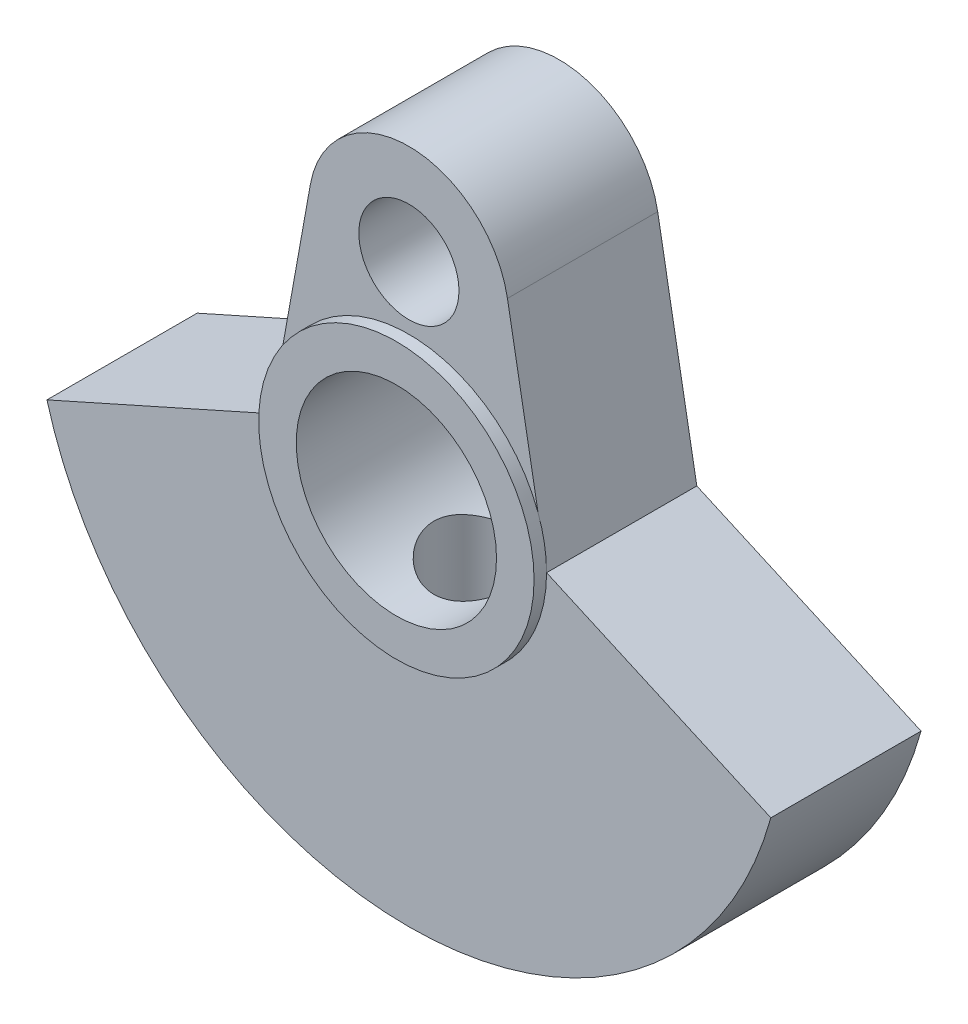
SolidWorks part; units mm, degrees
ref_plane "Front Plane" through (0, 0, 0) normal (0, 0, 1) x (1, 0, 0)
ref_plane "Top Plane" through (0, 0, 0) normal (0, 1, 0) x (1, 0, 0)
ref_plane "Right Plane" through (0, 0, 0) normal (1, 0, 0) x (0, 0, -1)
sketch "Sketch1" plane through (0, 0, 0) normal (0, 0, 1) x (1, 0, 0)
  line L0 (5.5, 0) -> (14.4568, -4)
  line L1 (0, 8) -> (0, 0) construction
  line L2 (-5.5, 0) -> (-14.4568, -4)
  line L3 (-5.5, 0) -> (-3.9371, 8.7067)
  line L4 (5.5, 0) -> (3.9371, 8.7067)
  circle A1 centre (0, 8) radius 2
  arc A2 (-14.4568, -4) -> (14.4568, -4) centre (0, 0) ccw
  arc A3 (3.9371, 8.7067) -> (-3.9371, 8.7067) centre (0, 8) ccw
  arc A4 (5.1566, 1.9129) -> (-5.1566, 1.9129) centre (0, 0) ccw
  circle A5 centre (0, 0) radius 4
  dimension "D2" = 8
  dimension "D3" = 4
  dimension "D5" = 15
  dimension "D6" = 8
  dimension "D1" = 8
  dimension "D4" = 4
extrude "Boss-Extrude1" add sketch "Sketch1" along normal blind 6
sketch "Sketch2" plane through (0, 0, 6) normal (0, 0, 1) x (1, 0, 0)
  circle A0 centre (0, 0) radius 5.5
  circle A1 centre (0, 0) radius 4
  dimension "D1" = 11
extrude "Boss-Extrude2" add sketch "Sketch2" along normal blind 0.5
sketch "Sketch3" plane through (0, 0, 0) normal (0, 1, 0) x (1, 0, 0)
  circle A0 centre (0, -3) radius 2
  dimension "D2" = 4
  dimension "D1" = 3
extrude "Cut-Extrude1" cut sketch "Sketch3" against normal up to surface and the other way up to surface from offset 5 up to face at (0, -9.5, 3) other way up to face at (4, 0, 0)
